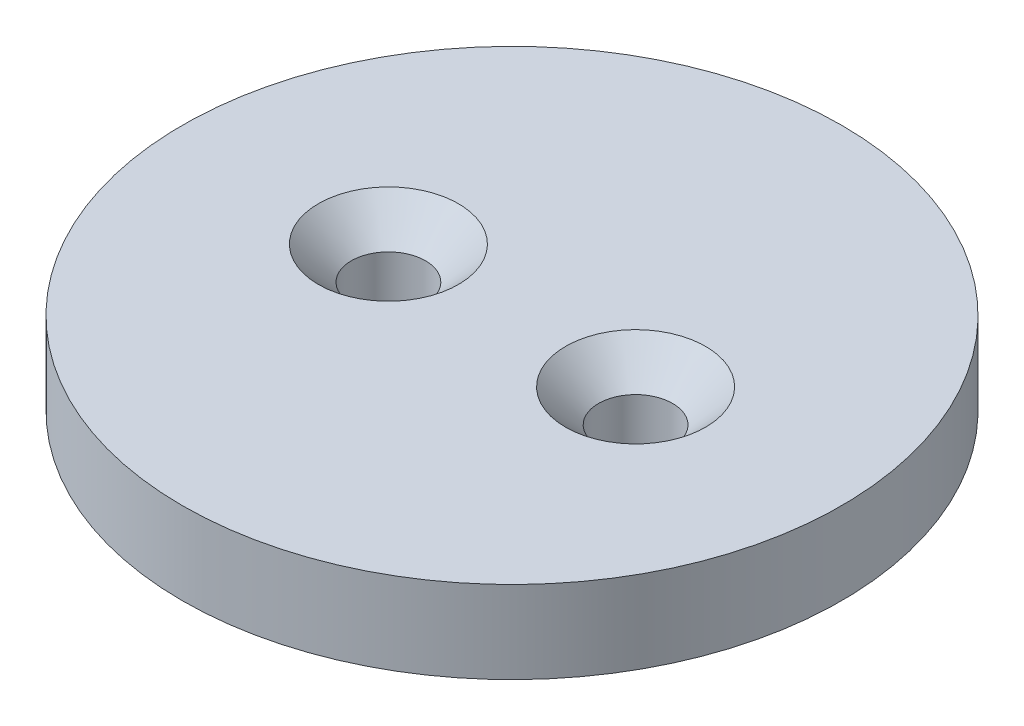
SolidWorks part; units mm, degrees
ref_plane "Front" through (0, 0, 0) normal (0, 0, 1) x (1, 0, 0)
ref_plane "Top" through (0, 0, 0) normal (0, 1, 0) x (1, 0, 0)
ref_plane "Right" through (0, 0, 0) normal (1, 0, 0) x (0, 0, -1)
sketch "Sketch1" plane through (0, 0, 0) normal (0, 1, 0) x (1, 0, 0)
  circle A0 centre (0, 0) radius 20
  dimension "D1" = 40
extrude "Boss-Extrude1" add sketch "Sketch1" along normal blind 5
sketch "Sketch2" plane through (0, 5, 0) normal (0, 1, 0) x (1, 0, 0)
  line L0 (-20, 0) -> (20, 0) construction
  line L1 (0, 20) -> (0, -20) construction
  circle A0 centre (0, 0) radius 20 construction
  circle A1 centre (-7.5, 0) radius 2.25
  circle A2 centre (7.5, 0) radius 2.25
  dimension "D3" = 4.5
  dimension "D4" = 4.5
  dimension "D1" = 15
  dimension "D2" = 7.5
extrude "Cut-Extrude1" cut sketch "Sketch2" against normal blind 5
chamfer "Chamfer1" distance 2 angle 45 2 edges at (7.5, 5, 2.25) (-7.5, 5, 2.25)
